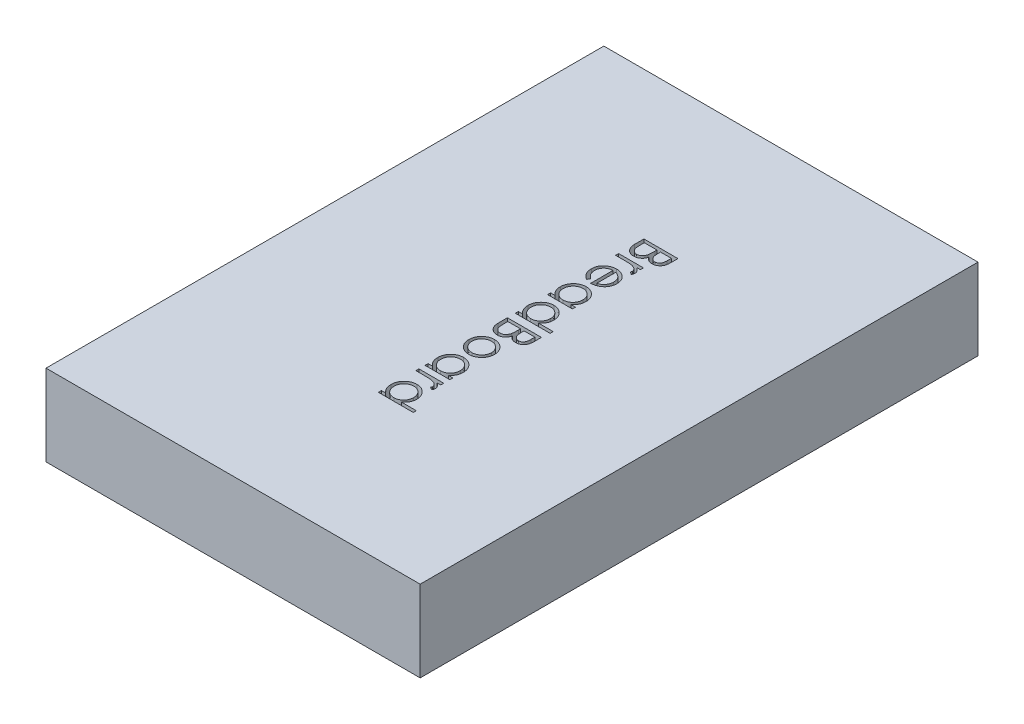
SolidWorks part; units mm, degrees
ref_plane "Front Plane" through (0, 0, 0) normal (0, 0, 1) x (1, 0, 0)
ref_plane "Top Plane" through (0, 0, 0) normal (0, 1, 0) x (1, 0, 0)
ref_plane "Right Plane" through (0, 0, 0) normal (1, 0, 0) x (0, 0, -1)
sketch "Sketch1" plane through (0, 0, 0) normal (0, 1, 0) x (1, 0, 0)
  line L1 (-118.1228, 56.3004) -> (-63.1228, 56.3004)
  line L2 (-118.1228, 56.3004) -> (-118.1228, -25.6996)
  line L3 (-118.1228, -25.6996) -> (-63.1228, -25.6996)
  line L4 (-63.1228, 56.3004) -> (-63.1228, -25.6996)
  line L5 (-118.1228, 56.3004) -> (-63.1228, -25.6996) construction
  line L6 (-118.1228, -25.6996) -> (-63.1228, 56.3004) construction
  point P0 (-90.6228, 15.3004)
  dimension "D1" = 55
  dimension "D2" = 82
extrude "Boss-Extrude1" add sketch "Sketch1" along normal blind 11.938
sketch "Sketch2" plane through (0, 11.938, 0) normal (0, 1, 0) x (1, 0, 0)
  line L0 (-118.1228, 15.3004) -> (-63.1228, 15.3004) construction
  line L1 (-118.1228, 56.3004) -> (-118.1228, -25.6996) construction
  line L2 (-63.1228, -25.6996) -> (-63.1228, 56.3004) construction
  line L3 (-90.6228, 56.3004) -> (-90.6228, -25.6996) construction
  line L4 (-63.1228, 56.3004) -> (-118.1228, 56.3004) construction
  line L5 (-118.1228, -25.6996) -> (-63.1228, -25.6996) construction
  text T0 "BreadBoard" font "Century Gothic" height 5
extrude "Cut-Extrude1" cut sketch "Sketch2" against normal blind 2.54
